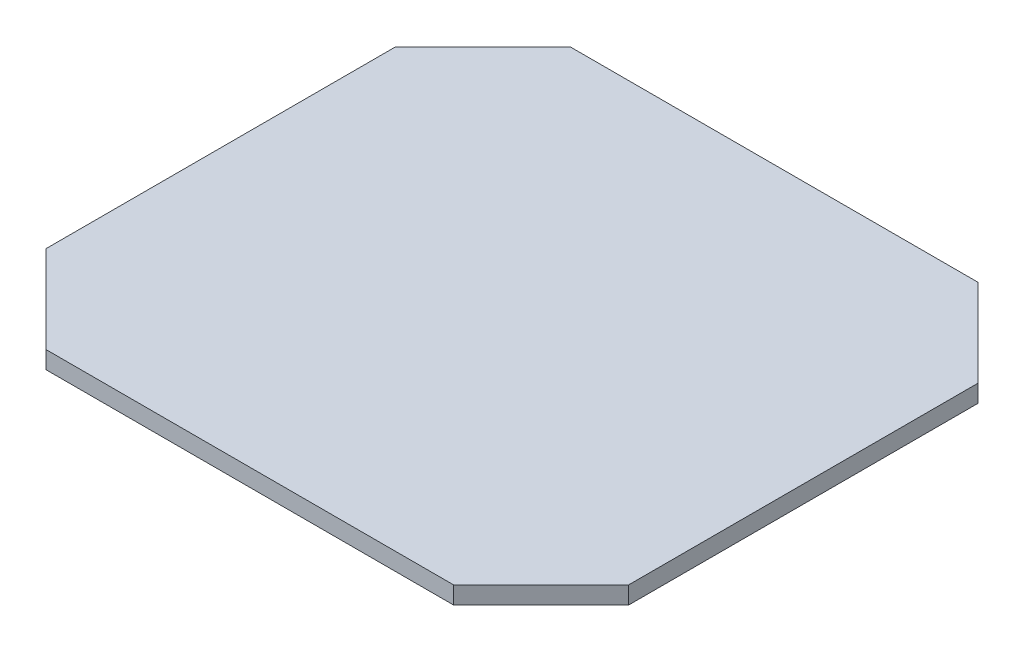
SolidWorks part; units mm, degrees
material "7075-T6 (SN)"
ref_plane "Plano frontal" through (0, 0, 0) normal (0, 0, 1) x (1, 0, 0)
ref_plane "Plano superior" through (0, 0, 0) normal (0, 1, 0) x (1, 0, 0)
ref_plane "Plano direito" through (0, 0, 0) normal (1, 0, 0) x (0, 0, -1)
sketch "Esboço1" plane through (0, 0, 0) normal (0, 1, 0) x (1, 0, 0)
  line L1 (-100, -90) -> (100, -90)
  line L2 (-100, -90) -> (-100, 90)
  line L3 (-100, 90) -> (100, 90)
  line L4 (100, -90) -> (100, 90)
  line L5 (-100, -90) -> (100, 90) construction
  line L6 (-100, 90) -> (100, -90) construction
  point P0 (0, 0)
  dimension "D1" = 180
  dimension "D2" = 200
extrude "Ressalto-extrusão1" add sketch "Esboço1" along normal mid plane 6
chamfer "Chanfro1" distance 30 angle 45 4 edges at (100, 0, 90) (100, 0, -90) (-100, 0, -90) (-100, 0, 90)
